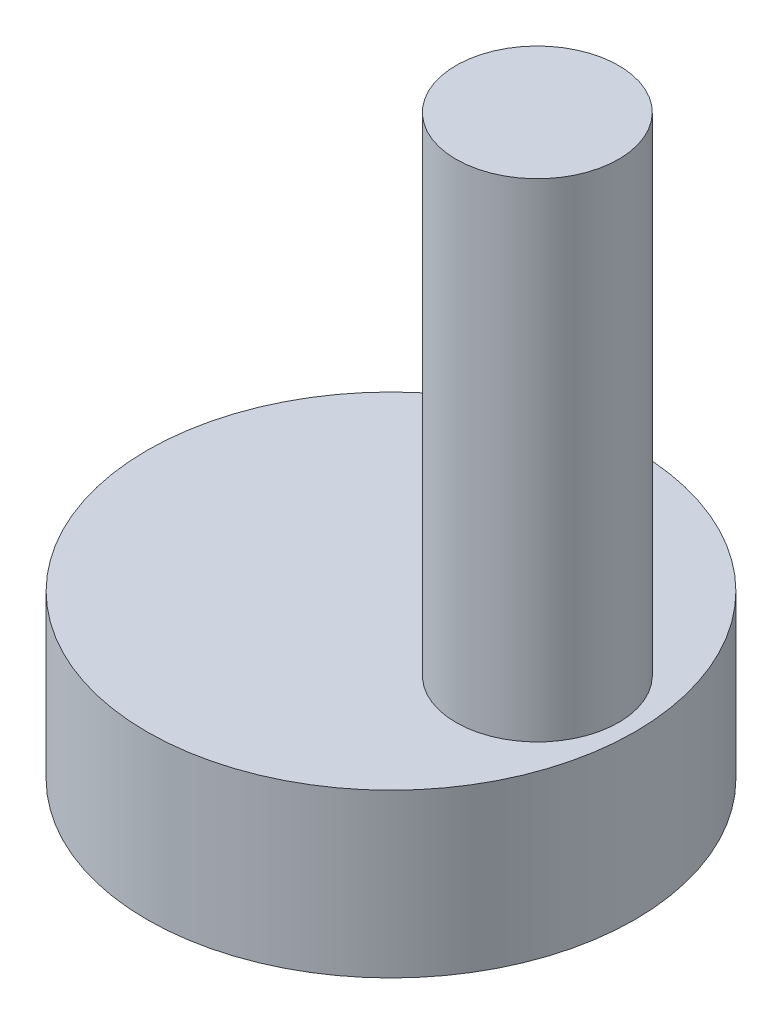
SolidWorks part; units mm, degrees
ref_plane "Front Plane" through (0, 0, 0) normal (0, 0, 1) x (1, 0, 0)
ref_plane "Top Plane" through (0, 0, 0) normal (0, 1, 0) x (1, 0, 0)
ref_plane "Right Plane" through (0, 0, 0) normal (1, 0, 0) x (0, 0, -1)
sketch "Sketch1" plane through (0, 0, 0) normal (0, 1, 0) x (1, 0, 0)
  circle A0 centre (0, 0) radius 15
  dimension "D1" = 30
extrude "Boss-Extrude1" add sketch "Sketch1" along normal blind 10
sketch "Sketch2" plane through (0, 10, 0) normal (0, 1, 0) x (1, 0, 0)
  line L0 (0, 0) -> (9, 0) construction
  circle A0 centre (9, 0) radius 5
  dimension "D2" = 10
  dimension "D1" = 9
extrude "Boss-Extrude2" add sketch "Sketch2" along normal blind 30
